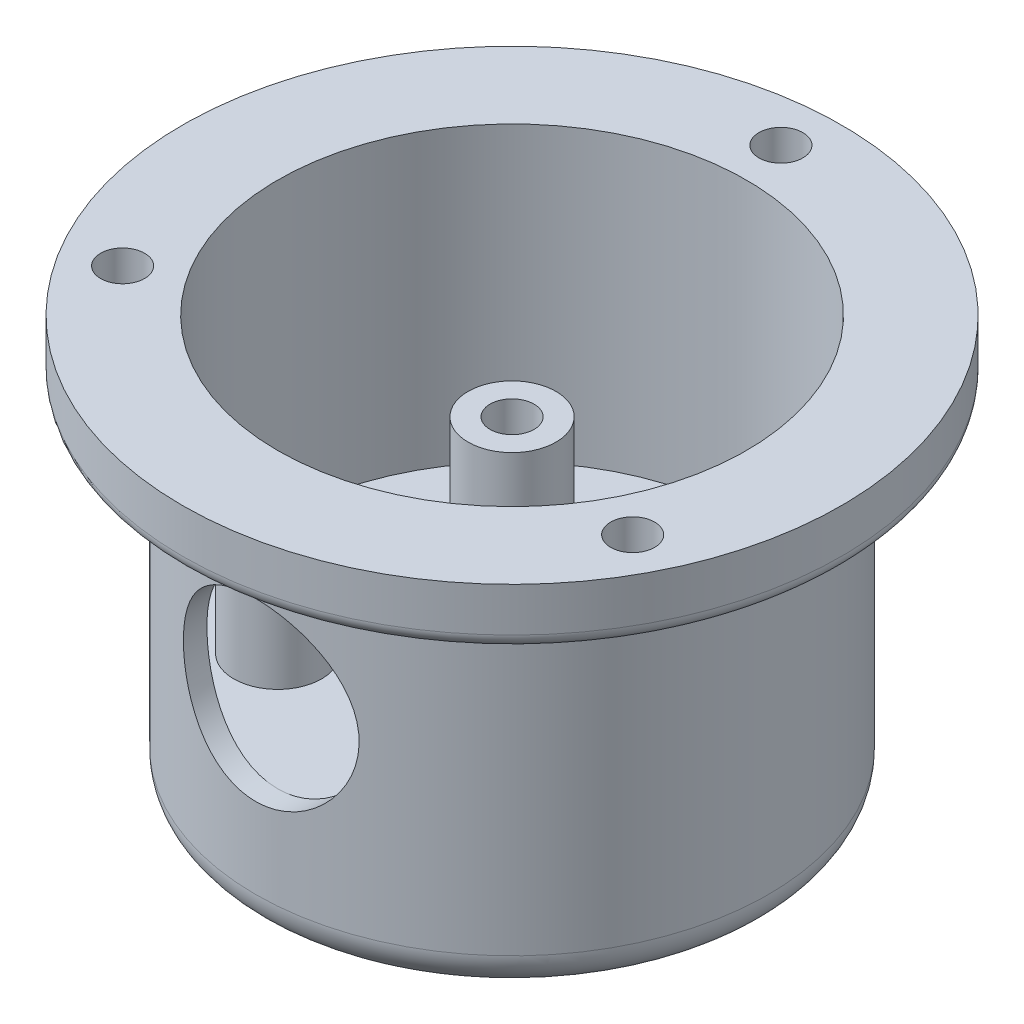
SolidWorks part; units mm, degrees
other "Markup1"
sketch "Sketch8" plane through (22.5, 4, 22.5) normal (0.0397, 0.615, 0.7876) x (0.9989, -0.0447, -0.0154)
sketch "Sketch11" plane through (22.5, 4, 22.5) normal (0.0397, 0.615, 0.7876) x (0.9989, -0.0447, -0.0154)
sketch "Sketch13" plane through (22.5, 4, 22.5) normal (0.0397, 0.615, 0.7876) x (0.9989, -0.0447, -0.0154)
other "Markup2"
sketch "Sketch9" plane through (22.5, 4, 22.5) normal (0.138, 0.6654, 0.7336) x (0.984, -0.0081, -0.1778)
sketch "Sketch12" plane through (22.5, 4, 22.5) normal (0.138, 0.6654, 0.7336) x (0.984, -0.0081, -0.1778)
sketch "Sketch14" plane through (22.5, 4, 22.5) normal (0.138, 0.6654, 0.7336) x (0.984, -0.0081, -0.1778)
ref_plane "Front Plane" through (0, 0, 0) normal (0, 0, 1) x (1, 0, 0)
ref_plane "Top Plane" through (0, 0, 0) normal (0, 1, 0) x (1, 0, 0)
ref_plane "Right Plane" through (0, 0, 0) normal (1, 0, 0) x (0, 0, -1)
sketch "Sketch1" plane through (0, 0, 0) normal (0, 1, 0) x (1, 0, 0)
  circle A2 centre (0, 0) radius 22.5
  dimension "D3" = 45
extrude "Boss-Extrude1" add sketch "Sketch1" along normal blind 4
sketch "Sketch2" plane through (0, 0, 0) normal (0, 1, 0) x (1, 0, 0)
  circle A0 centre (0, 0) radius 17.5
  dimension "D1" = 35
extrude "Boss-Extrude2" add sketch "Sketch2" against normal blind 24
sketch "Sketch3" plane through (0, 4, 0) normal (0, 1, 0) x (1, 0, 0)
  circle A0 centre (0, 0) radius 16
  dimension "D1" = 32
extrude "Cut-Extrude1" cut sketch "Sketch3" against normal blind 20
sketch "Sketch4" plane through (0, -16, 0) normal (0, 1, 0) x (1, 0, 0)
  circle A0 centre (-8, 8) radius 3
  circle A1 centre (8, 8) radius 3
  circle A2 centre (-8, -8) radius 3
  circle A3 centre (8, -8) radius 3
  dimension "D5" = 6
  dimension "D6" = 6
  dimension "D7" = 6
  dimension "D8" = 6
  dimension "D1" = 16
  dimension "D2" = 16
  dimension "D3" = 8
  dimension "D4" = 8
extrude "Boss-Extrude3" add sketch "Sketch4" along normal blind 6
ref_plane "Plane1" through (0, -10, 0) normal (0, 1, 0) x (1, 0, 0)
sketch "Sketch6" plane through (0, -10, 0) normal (0, 1, 0) x (1, 0, 0)
  circle A0 centre (-8, 8) radius 1.5
  circle A1 centre (8, 8) radius 1.5
  circle A2 centre (8, -8) radius 1.5
  circle A3 centre (-8, -8) radius 1.5
  point P12 (0, 0)
  dimension "D1" = 3
  dimension "D2" = 4
extrude "Cut-Extrude3" cut sketch "Sketch6" against normal blind 8
sketch "Sketch7" plane through (0, 4, 0) normal (0, 1, 0) x (1, 0, 0)
  circle A0 centre (0, 0) radius 19.25
  circle A1 centre (-0.8755, 19.2301) radius 1.5
  circle A2 centre (17.0915, -8.8568) radius 1.5
  circle A3 centre (-16.216, -10.3733) radius 1.5
  point P11 (0, 0)
  dimension "D1" = 38.5
  dimension "D2" = 3
  dimension "D3" = 3
extrude "Cut-Extrude4" cut sketch "Sketch7" against normal blind 10 contours A0 A1 | A0 A1 | A2 | A3
ref_plane "Plane2" through (0, 0, 17.5) normal (0, 0, 1) x (1, 0, 0)
sketch "Sketch10" plane through (0, 0, 17.5) normal (0, 0, 1) x (1, 0, 0)
  circle A0 centre (0, -10) radius 6
  dimension "D1" = 12
  dimension "D2" = 10
extrude "Cut-Extrude5" cut sketch "Sketch10" against normal up to surface (2.6676 mm away) contours A0
fillet "Fillet1" radius 2.5 1 edges at (0, -24, 17.5)
fillet "Fillet2" radius 1 1 edges at (0, 0, 22.5)
